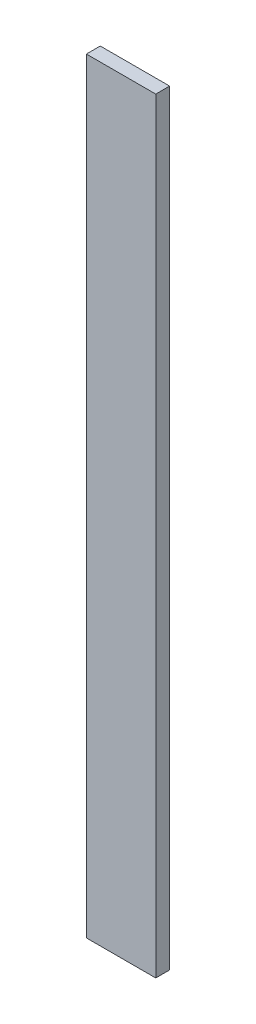
SolidWorks part; units mm, degrees
material "AISI 304"
ref_plane "Спереди" through (0, 0, 0) normal (0, 0, 1) x (1, 0, 0)
ref_plane "Сверху" through (0, 0, 0) normal (0, 1, 0) x (1, 0, 0)
ref_plane "Справа" through (0, 0, 0) normal (1, 0, 0) x (0, 0, -1)
other "Configuration Table"
sketch "Эскиз1" plane through (0, 0, 0) normal (0, 0, 1) x (1, 0, 0)
  line L1 (-7.5, -82.75) -> (7.5, -82.75)
  line L2 (-7.5, -82.75) -> (-7.5, 82.75)
  line L3 (-7.5, 82.75) -> (7.5, 82.75)
  line L4 (7.5, -82.75) -> (7.5, 82.75)
  line L5 (-7.5, -82.75) -> (7.5, 82.75) construction
  line L6 (-7.5, 82.75) -> (7.5, -82.75) construction
  point P0 (0, 0)
  dimension "D1" = 15
  dimension "D2" = 165.5
extrude "Бобышка-Вытянуть1" add sketch "Эскиз1" along normal blind 3
